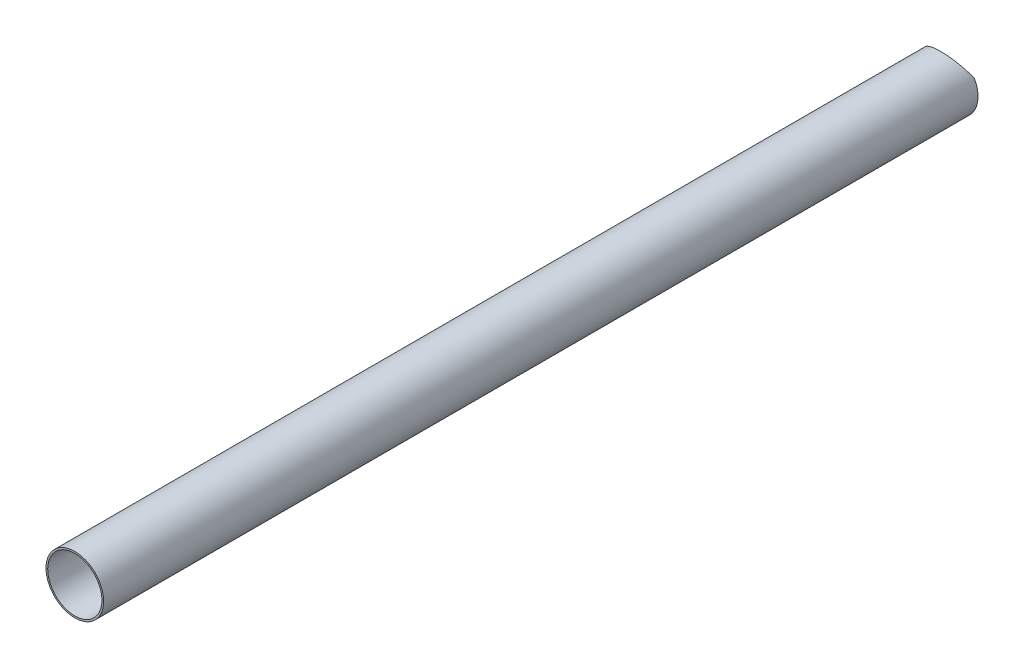
SolidWorks part; units mm, degrees
material "Carbon Fiber 110 MSI Test"
ref_plane "Front Plane" through (0, 0, 0) normal (0, 0, 1) x (1, 0, 0)
ref_plane "Top Plane" through (0, 0, 0) normal (0, 1, 0) x (1, 0, 0)
ref_plane "Right Plane" through (0, 0, 0) normal (1, 0, 0) x (0, 0, -1)
sketch "Sketch1" plane through (0, 0, 0) normal (1, 0, 0) x (0, 0, -1)
  line L0 (0, 0) -> (-51444.0805, 0) construction
  line L1 (0, 25.4) -> (0, 0) construction
  line L2 (0, 25.4) -> (819.15, 25.4)
  line L3 (0, 25.4) -> (0, 26.9875)
  line L4 (0, 26.9875) -> (819.15, 26.9875)
  line L5 (819.15, 25.4) -> (819.15, 26.9875)
  dimension "D1" = 50.8
  dimension "D2" = 819.15
  dimension "D3" = 1.5875
revolve "Revolve1" add sketch "Sketch1" angle 360 about L0
sketch "Sketch2" plane through (0, 0, 0) normal (1, 0, 0) x (0, 0, -1)
  line L0 (819.15, 13.2393) -> (811.2125, 26.9875)
  line L3 (811.2125, 26.9875) -> (819.15, 26.9875)
  line L4 (819.15, 26.9875) -> (819.15, 13.2393)
  line L5 (819.15, -26.9875) -> (819.15, 26.9875) construction
  line L6 (819.15, 26.9875) -> (0, 26.9875) construction
  point P2 (833.9763, -26.9875)
  point P3 (812.8, 26.9875)
  point P8 (0, 0)
  point P9 (812.8, 27.5456)
  point P10 (808.0375, 23.2894)
  point P11 (0, 0)
  dimension "D1" = 30
  dimension "D2" = 7.9375
extrude "Cut-Extrude1" cut sketch "Sketch2" against normal through all both and the other way through all
